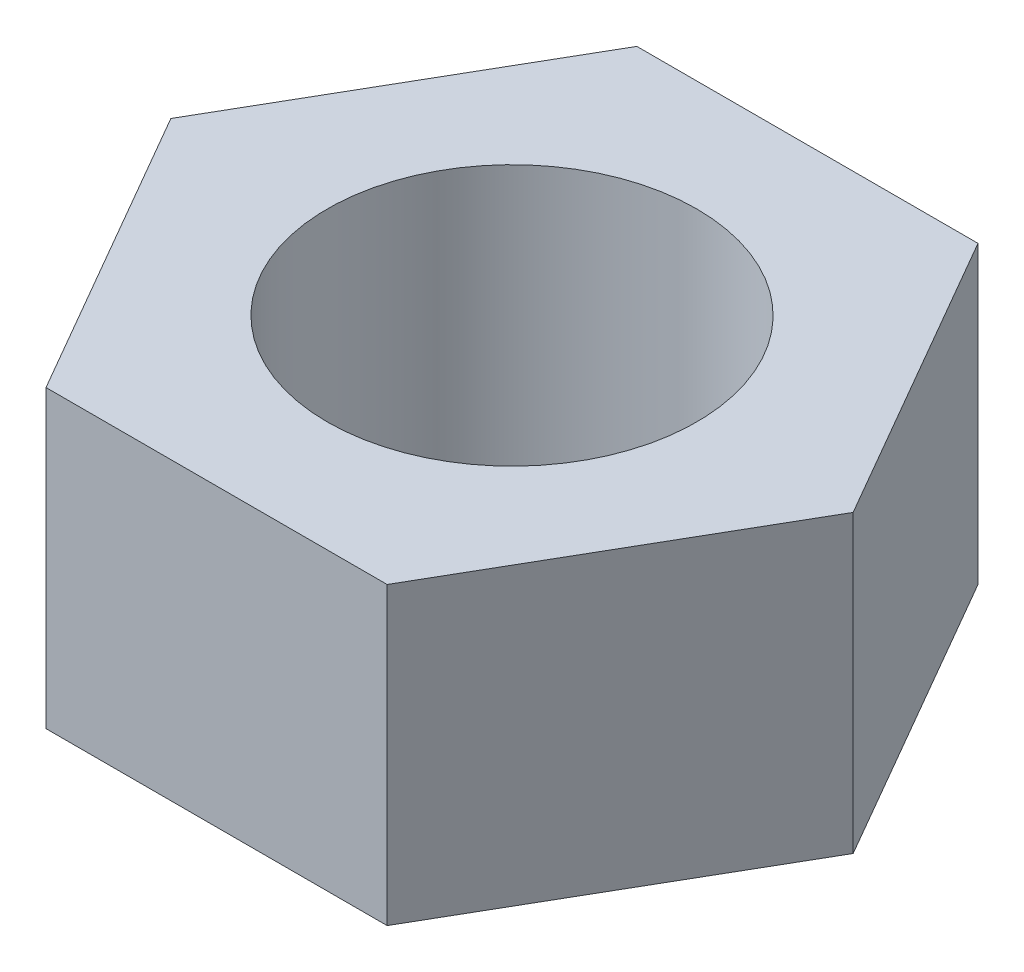
SolidWorks part; units mm, degrees
ref_plane "前视基准面" through (0, 0, 0) normal (0, 0, 1) x (1, 0, 0)
ref_plane "上视基准面" through (0, 0, 0) normal (0, 1, 0) x (1, 0, 0)
ref_plane "右视基准面" through (0, 0, 0) normal (1, 0, 0) x (0, 0, -1)
other "Configuration Table"
sketch "草图1" plane through (0, 0, 0) normal (0, 1, 0) x (1, 0, 0)
  line L1 (4.6188, 0) -> (2.3094, 4)
  line L2 (2.3094, 4) -> (-2.3094, 4)
  line L3 (-2.3094, 4) -> (-4.6188, 0)
  line L4 (-4.6188, 0) -> (-2.3094, -4)
  line L5 (-2.3094, -4) -> (2.3094, -4)
  line L6 (2.3094, -4) -> (4.6188, 0)
  circle A0 centre (0, 0) radius 4 construction
  circle A1 centre (0, 0) radius 2.5
  dimension "D2" = 5
  dimension "D1" = 8
extrude "凸台-拉伸1" add sketch "草图1" along normal blind 4
